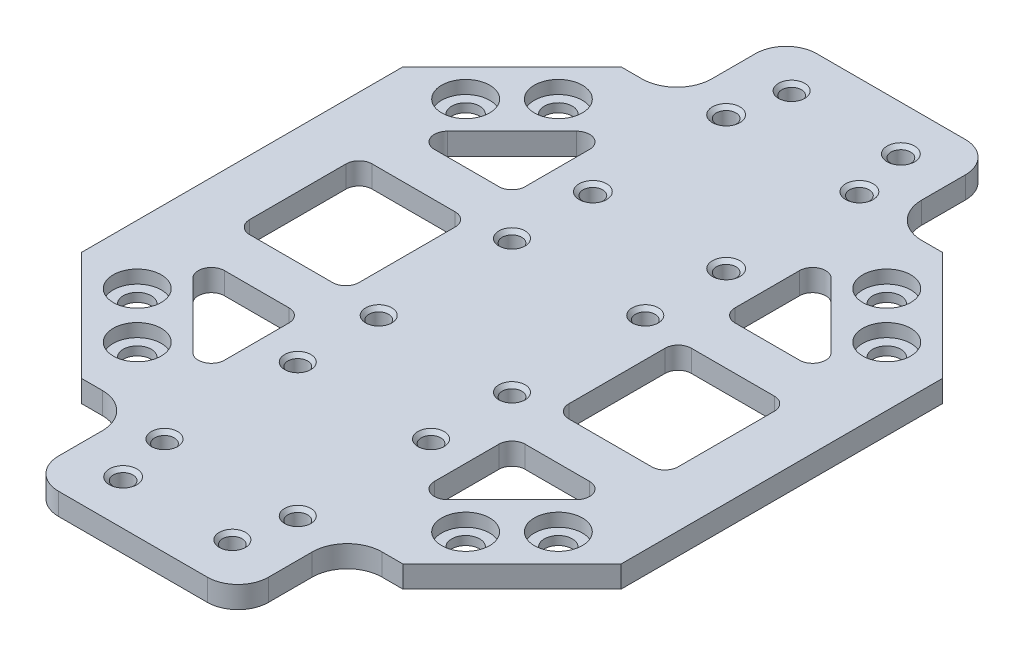
SolidWorks part; units mm, degrees
ref_plane "Front Plane" through (0, 0, 0) normal (0, 0, 1) x (1, 0, 0)
ref_plane "Top Plane" through (0, 0, 0) normal (0, 1, 0) x (1, 0, 0)
ref_plane "Right Plane" through (0, 0, 0) normal (1, 0, 0) x (0, 0, -1)
sketch "Sketch2" plane through (0, 0, 0) normal (0, 1, 0) x (1, 0, 0)
  line L1 (-61.75, -61.75) -> (61.75, -61.75)
  line L2 (-61.75, -61.75) -> (-61.75, 61.75)
  line L3 (-61.75, 61.75) -> (61.75, 61.75)
  line L4 (61.75, -61.75) -> (61.75, 61.75)
  line L5 (-61.75, -61.75) -> (61.75, 61.75) construction
  line L6 (-61.75, 61.75) -> (61.75, -61.75) construction
  line L21 (-61.75, 61.75) -> (-61.75, 36.75)
  line L22 (-61.75, 36.75) -> (-36.75, 61.75)
  line L23 (-36.75, 61.75) -> (-61.75, 61.75)
  line L24 (61.75, 61.75) -> (36.75, 61.75)
  line L25 (36.75, 61.75) -> (61.75, 36.75)
  line L26 (61.75, 36.75) -> (61.75, 61.75)
  line L27 (61.75, -61.75) -> (61.75, -36.75)
  line L28 (61.75, -36.75) -> (36.75, -61.75)
  line L29 (36.75, -61.75) -> (61.75, -61.75)
  line L32 (-61.75, -61.75) -> (-36.75, -61.75)
  line L33 (-36.75, -61.75) -> (-61.75, -36.75)
  line L34 (-61.75, -36.75) -> (-61.75, -61.75)
  line L35 (-61.75, -36.75) -> (-49.0221, -24.0221)
  line L36 (-36.75, -61.75) -> (-24.0221, -49.0221)
  line L37 (-24.0221, -49.0221) -> (-49.0221, -24.0221)
  line L38 (-36.75, 61.75) -> (-24.0221, 49.0221)
  line L39 (-49.0221, 24.0221) -> (-24.0221, 49.0221)
  line L40 (-61.75, 36.75) -> (-49.0221, 24.0221)
  line L41 (61.75, 36.75) -> (49.0221, 24.0221)
  line L42 (24.0221, 49.0221) -> (49.0221, 24.0221)
  line L43 (36.75, 61.75) -> (24.0221, 49.0221)
  line L44 (36.75, -61.75) -> (24.0221, -49.0221)
  line L45 (49.0221, -24.0221) -> (24.0221, -49.0221)
  line L46 (61.75, -36.75) -> (49.0221, -24.0221)
  line L47 (-55, 0) -> (55, 0) construction
  line L48 (-24.0221, -61.75) -> (24.0221, -61.75)
  line L49 (-24.0221, -61.75) -> (-24.0221, -86.75)
  line L50 (-24.0221, -86.75) -> (24.0221, -86.75)
  line L51 (24.0221, -61.75) -> (24.0221, -86.75)
  line L52 (-24.0221, 86.75) -> (24.0221, 86.75)
  line L53 (24.0221, 61.75) -> (24.0221, 86.75)
  line L54 (-24.0221, 61.75) -> (24.0221, 61.75)
  line L55 (-24.0221, 61.75) -> (-24.0221, 86.75)
  line L61 (-22.5, -68.5) -> (22.5, 68.5) construction
  line L62 (-22.5, 68.5) -> (22.5, -68.5) construction
  line L65 (-22.5, -68.5) -> (22.5, 68.5) construction
  line L66 (-22.5, 68.5) -> (22.5, -68.5) construction
  line L71 (22.5, 68.5) -> (-22.5, -68.5) construction
  line L72 (22.5, -68.5) -> (-22.5, 68.5) construction
  line L77 (0, 0) -> (0, -16.8472)
  line L81 (61.75, -61.75) -> (36.75, -61.75)
  circle A0 centre (12.5, -76.5) radius 2.25
  circle A1 centre (-12.5, -76.5) radius 2.25
  circle A2 centre (12.5, 76.5) radius 2.25
  circle A3 centre (-12.5, 76.5) radius 2.25
  point P0 (0, 0)
  point P20 (0.597, -0.5877)
  point P21 (0, 0)
  point P35 (-0.0454, 0)
  point P36 (0, 0)
  point P41 (0, 0)
  point P49 (0, 0)
  point P55 (0, 0)
  dimension "D1" = 4
extrude "Boss-Extrude2" add sketch "Sketch2" along normal blind 5
fillet "Fillet1" radius 8 4 edges at (-24.0221, 2.5, -61.75) (24.0221, 2.5, -61.75) (-24.0221, 2.5, 61.75) (24.0221, 2.5, 61.75)
fillet "Fillet2" radius 7 4 edges at (-24.0221, 2.5, -86.75) (24.0221, 2.5, -86.75) (-24.0221, 2.5, 86.75) (24.0221, 2.5, 86.75)
sketch "Sketch5" plane through (0, 0, 0) normal (0, -1, 0) x (1, 0, 0)
  line L0 (-49.25, 49.25) -> (-36.8756, 61.6244)
  line L1 (-36.75, 61.75) -> (-61.75, 36.75) construction
  line L2 (-36.8756, 61.6244) -> (-24.1477, 48.8964)
  line L3 (-24.1477, 48.8964) -> (-36.5221, 36.5221)
  line L4 (-49.25, 49.25) -> (-61.6244, 36.8756)
  line L5 (-61.6244, 36.8756) -> (-48.8964, 24.1477)
  line L6 (-48.8964, 24.1477) -> (-36.5221, 36.5221)
  line L8 (-36.5221, 36.5221) -> (-39.2047, 39.2047)
  circle A0 centre (-37.5827, 48.1893) radius 3.2
  circle A1 centre (-48.1893, 37.5827) radius 3.2
  circle A4 centre (48.1893, 37.5827) radius 3.2
  circle A5 centre (37.5827, 48.1893) radius 3.2
  circle A6 centre (37.5827, -48.1893) radius 3.2
  circle A7 centre (48.1893, -37.5827) radius 3.2
  circle A8 centre (-48.1893, -37.5827) radius 3.2
  circle A9 centre (-37.5827, -48.1893) radius 3.2
  point P28 (0, 0)
  dimension "D1" = 4
extrude "Cut-Extrude2" cut sketch "Sketch5" against normal up to surface (5 mm away) contours A0 | A1 | A4 | A5 | A7 | A6 | A9 | A8 up to face at (0, 5, 0)
sketch "Sketch6" plane through (0, 0, 0) normal (0, -1, 0) x (1, 0, 0)
  circle A0 centre (-37.5827, 48.1893) radius 3
  circle A1 centre (-48.1893, 37.5827) radius 3
  circle A2 centre (37.5827, 48.1893) radius 3
  circle A3 centre (48.1893, 37.5827) radius 3
  circle A4 centre (48.1893, -37.5827) radius 3
  circle A5 centre (37.5827, -48.1893) radius 3
  circle A6 centre (-37.5827, -48.1893) radius 3
  circle A7 centre (-48.1893, -37.5827) radius 3
  point P21 (0, 0)
extrude "Cut-Extrude3" [suppressed] cut sketch "Sketch6" against normal blind 3
chamfer "Chamfer1" distance 0.75 angle 50 4 edges at (12.5, 5, 78.75) (-12.5, 5, 78.75) (-12.5, 5, -74.25) (12.5, 5, -74.25)
sketch "Sketch7" plane through (0, 5, 0) normal (0, 1, 0) x (1, 0, 0)
  circle A0 centre (-37.5827, 48.1893) radius 5.5
  circle A1 centre (-48.1893, 37.5827) radius 5.5
  circle A2 centre (37.5827, 48.1893) radius 5.5
  circle A3 centre (48.1893, 37.5827) radius 5.5
  circle A4 centre (48.1893, -37.5827) radius 5.5
  circle A5 centre (37.5827, -48.1893) radius 5.5
  circle A6 centre (-37.5827, -48.1893) radius 5.5
  circle A7 centre (-48.1893, -37.5827) radius 5.5
  point P21 (0, 0)
  dimension "D1" = 4
extrude "Cut-Extrude4" cut sketch "Sketch7" against normal blind 3
sketch "Sketch8" plane through (0, 5, 0) normal (0, 1, 0) x (1, 0, 0)
  line L0 (15.2378, -33.7721) -> (-15.2622, -33.7721)
  line L1 (-24.0221, 69.75) -> (-24.0221, 79.75) construction
  line L2 (49.0221, -24.0221) -> (24.0221, -24.0221)
  line L3 (15.2378, -33.7721) -> (15.2378, -64.2721)
  line L4 (24.0221, -24.0221) -> (24.0221, -49.0221)
  line L5 (49.0221, -24.0221) -> (24.0221, -49.0221)
  line L11 (15.2378, -64.2721) -> (-15.2622, -64.2721)
  line L12 (-15.2622, -33.7721) -> (-15.2622, -64.2721)
  line L13 (15.25, 15.25) -> (-15.25, 15.25)
  line L14 (15.25, 15.25) -> (15.25, -15.25)
  line L15 (15.25, -15.25) -> (-15.25, -15.25)
  line L16 (-15.25, 15.25) -> (-15.25, -15.25)
  line L17 (15.25, 15.25) -> (-15.25, -15.25) construction
  line L18 (15.25, -15.25) -> (-15.25, 15.25) construction
  line L22 (61.75, -36.75) -> (36.75, -61.75)
  line L23 (61.75, -36.75) -> (49.0221, -24.0221)
  line L24 (36.75, -61.75) -> (24.0221, -49.0221)
  line L25 (49.0221, -24.0221) -> (24.0221, -49.0221)
  line L26 (-36.75, -61.75) -> (-61.75, -36.75)
  line L27 (-36.75, -61.75) -> (-24.0221, -49.0221)
  line L28 (-24.0221, -49.0221) -> (-49.0221, -24.0221)
  line L29 (-61.75, -36.75) -> (-49.0221, -24.0221)
  line L30 (-61.75, 36.75) -> (-36.75, 61.75)
  line L31 (-61.75, 36.75) -> (-49.0221, 24.0221)
  line L32 (-49.0221, 24.0221) -> (-24.0221, 49.0221)
  line L33 (-36.75, 61.75) -> (-24.0221, 49.0221)
  line L34 (36.75, 61.75) -> (61.75, 36.75)
  line L35 (36.75, 61.75) -> (24.0221, 49.0221)
  line L36 (24.0221, 49.0221) -> (49.0221, 24.0221)
  line L37 (61.75, 36.75) -> (49.0221, 24.0221)
  line L38 (15.2378, -33.7721) -> (-15.2622, -64.2721) construction
  line L39 (15.2378, -64.2721) -> (-15.2622, -33.7721) construction
  line L41 (-24.0221, -49.0221) -> (-24.0221, -24.0221)
  line L42 (-24.0221, -24.0221) -> (-49.0221, -24.0221)
  line L43 (-49.0221, 24.0221) -> (-24.0221, 24.0221)
  line L44 (-24.0221, 24.0221) -> (-24.0221, 49.0221)
  line L45 (24.0221, 49.0221) -> (24.0221, 24.0221)
  line L46 (24.0221, 24.0221) -> (49.0221, 24.0221)
  line L47 (0, 0) -> (-11.4563, 0)
  line L48 (15.2378, 64.2721) -> (-15.2622, 33.7721) construction
  line L49 (15.2378, 33.7721) -> (-15.2622, 64.2721) construction
  line L50 (-15.2622, 33.7721) -> (-15.2622, 64.2721)
  line L51 (15.2378, 64.2721) -> (-15.2622, 64.2721)
  line L52 (15.2378, 33.7721) -> (15.2378, 64.2721)
  line L53 (15.2378, 33.7721) -> (-15.2622, 33.7721)
  circle A0 centre (-15.25, -15.25) radius 2.25
  circle A1 centre (-15.25, 15.25) radius 2.25
  circle A2 centre (15.25, 15.25) radius 2.25
  circle A3 centre (15.25, -15.25) radius 2.25
  circle A4 centre (-15.2622, -64.2721) radius 2.25
  circle A5 centre (-15.2622, -33.7721) radius 2.25
  circle A6 centre (15.2378, -33.7721) radius 2.25
  circle A7 centre (15.2378, -64.2721) radius 2.25
  circle A8 centre (15.2378, 64.2721) radius 2.25
  circle A9 centre (15.2378, 33.7721) radius 2.25
  circle A10 centre (-15.2622, 33.7721) radius 2.25
  circle A11 centre (-15.2622, 64.2721) radius 2.25
  point P0 (-0.3974, -50.0038)
  point P1 (-0.0122, -49.0221)
  point P12 (0, 0)
  point P14 (-0.3974, -50.0038)
  point P15 (-0.3974, -50.0038)
  point P18 (0, 0)
  point P33 (0, 0)
  point P54 (0, 0)
  point P56 (-0.0122, -49.0221)
  point P66 (0, 0)
  point P74 (-0.0122, 49.0221)
  point P75 (-0.3974, 50.0038)
  dimension "D1" = 4
  dimension "D2" = 4
  dimension "D3" = 4
  dimension "D4" = 4
extrude "Cut-Extrude5" cut sketch "Sketch8" against normal blind 10 contours L3 A6 L0 | L0 A6 L3 | L0 A5 L12 | L12 A5 L0 | L12 A4 L11 | L11 A4 L12 | L11 A7 L3 | L3 A7 L11 | L15 A3 L14 | L14 A3 L15 | L16 A0 L15 | L15 A0 L16 | L14 A2 L13 | L13 A2 L14 | L13 A1 L16 | L16 A1 L13 | A8 | A9 | A10 | A11
sketch "Sketch9" plane through (0, 5, 0) normal (0, 1, 0) x (1, 0, 0)
  line L0 (61.75, -36.75) -> (36.75, -61.75)
  line L1 (61.75, -36.75) -> (49.0221, -24.0221)
  line L2 (36.75, -61.75) -> (24.0221, -49.0221)
  line L3 (49.0221, -24.0221) -> (24.0221, -49.0221)
  line L4 (-36.75, -61.75) -> (-24.0221, -49.0221)
  line L5 (-36.75, -61.75) -> (-61.75, -36.75)
  line L6 (-24.0221, -49.0221) -> (-49.0221, -24.0221)
  line L7 (-61.75, -36.75) -> (-49.0221, -24.0221)
  line L8 (-61.75, 36.75) -> (-49.0221, 24.0221)
  line L9 (-61.75, 36.75) -> (-36.75, 61.75)
  line L10 (-49.0221, 24.0221) -> (-24.0221, 49.0221)
  line L11 (-36.75, 61.75) -> (-24.0221, 49.0221)
  line L12 (36.75, 61.75) -> (24.0221, 49.0221)
  line L13 (36.75, 61.75) -> (61.75, 36.75)
  line L14 (24.0221, 49.0221) -> (49.0221, 24.0221)
  line L15 (61.75, 36.75) -> (49.0221, 24.0221)
  line L16 (49.0221, -24.0221) -> (24.0221, -24.0221)
  line L17 (24.0221, -24.0221) -> (24.0221, -49.0221)
  line L18 (-24.0221, -24.0221) -> (-49.0221, -24.0221)
  line L19 (-24.0221, -49.0221) -> (-24.0221, -24.0221)
  line L20 (-24.0221, 24.0221) -> (-24.0221, 49.0221)
  line L21 (-49.0221, 24.0221) -> (-24.0221, 24.0221)
  line L22 (24.0221, 24.0221) -> (49.0221, 24.0221)
  line L23 (24.0221, 49.0221) -> (24.0221, 24.0221)
  line L24 (49.0221, -24.0221) -> (49.0221, -14.0221)
  line L25 (24.0221, 24.0221) -> (24.0221, 14.0221)
  line L26 (0, 0) -> (0, -17.6815)
  line L27 (49.0221, -14.0221) -> (24.0221, -14.0221)
  line L28 (49.0221, -14.0221) -> (49.0221, 14.0221)
  line L29 (49.0221, 14.0221) -> (24.0221, 14.0221)
  line L30 (24.0221, -14.0221) -> (24.0221, 14.0221)
  line L31 (-49.0221, 14.0221) -> (-24.0221, 14.0221)
  line L32 (-24.0221, -14.0221) -> (-24.0221, 14.0221)
  line L33 (-49.0221, -14.0221) -> (-24.0221, -14.0221)
  line L34 (-49.0221, -14.0221) -> (-49.0221, 14.0221)
  point P21 (0, 0)
  point P32 (0, 0)
  dimension "D1" = 4
  dimension "D2" = 4
extrude "Cut-Extrude7" cut sketch "Sketch9" against normal blind 10 contours L30 L27 L28 L29 | L16 L17 L3 | L6 L19 L18 | L34 L33 L32 L31 | L10 L21 L20 | L14 L23 L22
fillet "Fillet3" radius 3 20 edges at (-24.0221, 2.5, -24.0221) (-49.0221, 2.5, -24.0221) (-24.0221, 2.5, -49.0221) (49.0221, 2.5, -24.0221) (24.0221, 2.5, -49.0221) (24.0221, 2.5, -24.0221) (-24.0221, 2.5, -14.0221) (-49.0221, 2.5, -14.0221) (-49.0221, 2.5, 14.0221) (-24.0221, 2.5, 14.0221) (-24.0221, 2.5, 24.0221) (-49.0221, 2.5, 24.0221) (-24.0221, 2.5, 49.0221) (49.0221, 2.5, -14.0221) (24.0221, 2.5, -14.0221) (49.0221, 2.5, 14.0221) (24.0221, 2.5, 14.0221) (49.0221, 2.5, 24.0221) (24.0221, 2.5, 24.0221) (24.0221, 2.5, 49.0221)
chamfer "Chamfer2" distance 0.75 angle 50 12 edges at (15.2378, 5, 66.5221) (-15.2622, 5, 66.5221) (-15.2622, 5, 36.0221) (15.2378, 5, 36.0221) (-15.25, 5, 17.5) (15.25, 5, 17.5) (15.25, 5, -13) (-15.25, 5, -13) (-15.2622, 5, -36.0221) (15.2378, 5, -36.0221) (-15.2622, 5, -66.5221) (15.2378, 5, -66.5221)
